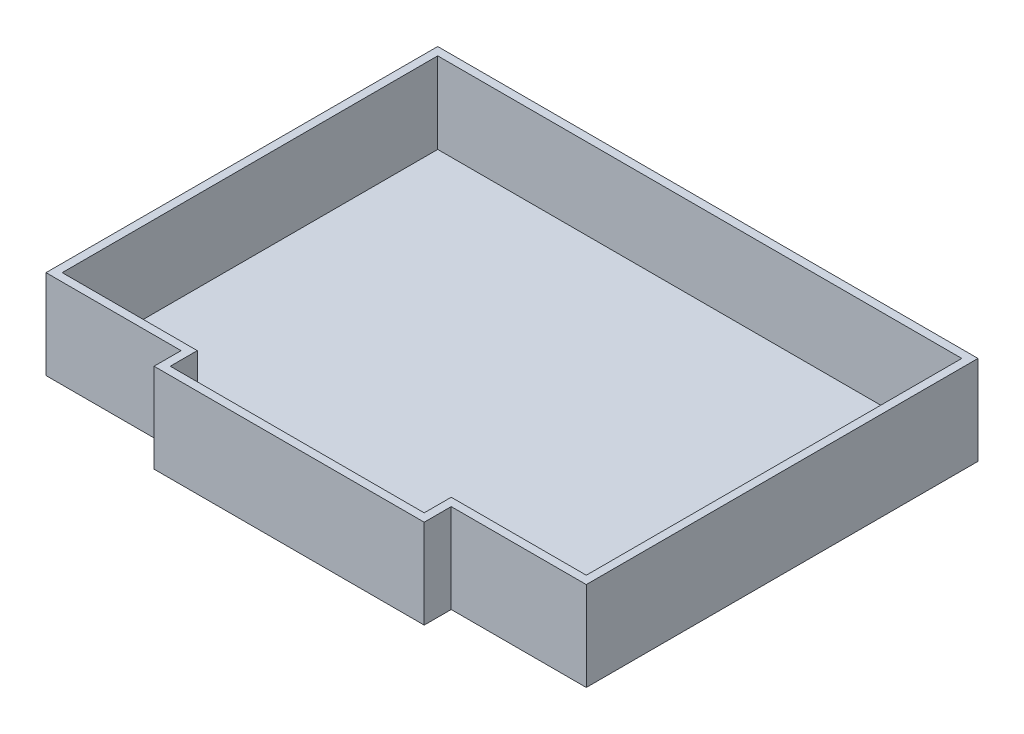
SolidWorks part; units mm, degrees
material "ABS"
ref_plane "Alzado" through (0, 0, 0) normal (0, 0, 1) x (1, 0, 0)
ref_plane "Planta" through (0, 0, 0) normal (0, 1, 0) x (1, 0, 0)
ref_plane "Vista lateral" through (0, 0, 0) normal (1, 0, 0) x (0, 0, -1)
sketch "Croquis1" plane through (0, 0, 0) normal (0, 1, 0) x (1, 0, 0)
  line L1 (50, 20) -> (150, 20)
  line L2 (0, 30) -> (0, 175)
  line L3 (0, 175) -> (200, 175)
  line L4 (200, 30) -> (200, 175)
  line L7 (0, 30) -> (50, 30)
  line L8 (50, 20) -> (50, 30)
  line L11 (200, 30) -> (150, 30)
  line L12 (150, 20) -> (150, 30)
  dimension "D1" = 155
  dimension "D2" = 200
  dimension "D3" = 50
  dimension "D4" = 50
  dimension "D5" = 10
extrude "Saliente-Extruir1" add sketch "Croquis1" along normal blind 3
sketch "Croquis2" plane through (0, 3, 0) normal (0, 1, 0) x (1, 0, 0)
  line L0 (0, 175) -> (200, 175)
  line L1 (200, 175) -> (200, 30)
  line L2 (200, 30) -> (150, 30)
  line L3 (150, 30) -> (150, 20)
  line L4 (150, 20) -> (50, 20)
  line L5 (50, 20) -> (50, 30)
  line L6 (50, 30) -> (0, 30)
  line L7 (0, 30) -> (0, 175)
  line L16 (197, 33) -> (197, 172)
  line L17 (197, 172) -> (3, 172)
  line L18 (3, 172) -> (3, 33)
  line L19 (3, 33) -> (53, 33)
  line L20 (53, 33) -> (53, 23)
  line L21 (53, 23) -> (147, 23)
  line L22 (147, 23) -> (147, 33)
  line L23 (147, 33) -> (197, 33)
  line L24 (197, 33) -> (197, 172)
  line L25 (197, 172) -> (3, 172)
  line L26 (3, 172) -> (3, 33)
  line L27 (3, 33) -> (53, 33)
  line L28 (53, 33) -> (53, 23)
  line L29 (53, 23) -> (147, 23)
  line L30 (147, 23) -> (147, 33)
  line L31 (147, 33) -> (197, 33)
  dimension "D1" = 3
extrude "Saliente-Extruir2" add sketch "Croquis2" along normal blind 30
